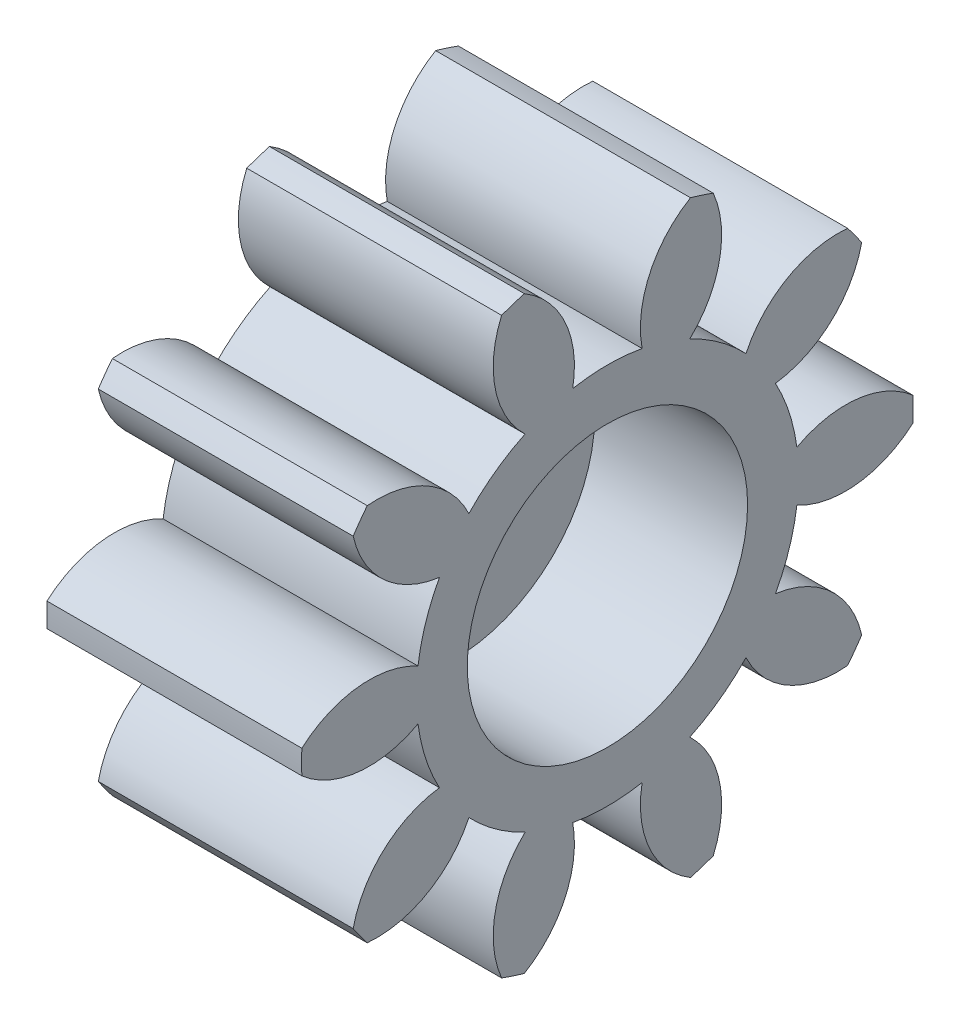
SolidWorks part; units mm, degrees
ref_plane "Plane1" through (0, 0, 0) normal (0, 0, 1) x (1, 0, 0)
ref_plane "Plane2" through (0, 0, 0) normal (0, 1, 0) x (1, 0, 0)
ref_plane "Plane3" through (0, 0, 0) normal (1, 0, 0) x (0, 0, -1)
sketch "HoldingSke" plane through (0, 0, 0) normal (0, 1, 0) x (1, 0, 0)
  line L0 (0, 0) -> (0.9848, -0.1736)
  line L1 (-15, 0) -> (100, 0) construction
  line L2 (0, 0) -> (-2.1039, 2.3779)
  line L3 (0, 0) -> (-11.863, 4.5341)
  line L4 (0, 0) -> (8.5048, 1.4996)
  line L5 (0, 0) -> (-46.8476, -17.4728)
  line L6 (0, 0) -> (-4.1448, -2.7965)
  line L7 (-2.1039, 2.3779) -> (8.6586, 51.2059)
  line L8 (-76.2, 54.61) -> (-75.7, 54.61)
  line L9 (-67.7845, 28.3722) -> (-49.3413, 33.142)
  line L10 (-76.2, 71.12) -> (104.1128, 71.12)
  line L11 (0, 0) -> (-5, 0)
  line L12 (-76.2, 101.6) -> (-76.162, 101.6)
  line L13 (24.9733, 27.94) -> (52.9518, 28.4284)
  line L14 (24.9733, 27.94) -> (24.9743, 27.94)
  line L15 (24.9733, 27.94) -> (100.4006, 29.5858)
  line L16 (-63.627, -1) -> (-12.827, -1)
  circle A0 centre (0, 0) radius 1.5
  circle A1 centre (0, 0) radius 3.749
  circle A2 centre (0, 0) radius 37.5
  circle A3 centre (0, 0) radius 1.5
  dimension "MHD" = 7.498
  dimension "Hub_dia" = 75
  dimension "Bore" = 3
  dimension "MBD" = 3
  dimension "Num_teeth" = 10
  dimension "Pitch" = 1
  dimension "Overall_len" = 50
  dimension "Show_teeth" = 10
  dimension "Thickness" = 5
  dimension "OAL" = 50.0001
  dimension "T_dim" = 0.5
  dimension "Ap" = 14.5
  dimension "H" = 19.05
  dimension "Pitch_radius" = 180.3128
  dimension "Width" = 5
  dimension "Backlash" = 0.038
  dimension "Addendum_fac" = 1
  dimension "Dedendum_fac" = 1.25
  dimension "Clearance_fac" = 0.25
  dimension "Dedendum_add" = 0.001
  dimension "Module" = 1
sketch "BasProSke" plane through (0, 0, 0) normal (0, 1, 0) x (1, 0, 0)
  line L0 (-10, 0) -> (60, 0) construction
  line L1 (0, 0) -> (0, 6)
  line L2 (0, 0) -> (5, 0)
  line L3 (5, 0) -> (5, 6)
  line L4 (5, 6) -> (0, 6)
  dimension "Thickness" = 5
  dimension "Diameter" = 12
revolve "Base-Revolve" add sketch "BasProSke" angle 360 about L0
sketch "TooCutSke" plane through (0, 0, 0) normal (1, 0, 0) x (0, 0, -1)
  line L1 (0, 0) -> (0, 107) construction
  line L2 (0, 0) -> (-0.8485, 4.9275) construction
  line L3 (0, 0) -> (-3.0584, 9.4126) construction
  line L4 (-0.8485, 4.9275) -> (-1.5292, 4.7063) construction
  arc A0 (0.6809, 3.6866) -> (-0.6809, 3.6866) centre (0, 0) ccw
  arc A1 (1.66, 5.7922) -> (-1.66, 5.7922) centre (0, 0) ccw
  circle A2 centre (0, 0) radius 5 construction
  circle A3 centre (0, 0) radius 4.8407 construction
  arc A4 (-0.6809, 3.6866) -> (-1.66, 5.7922) centre (-2.6471, 4.0528) ccw
  arc A5 (1.66, 5.7922) -> (0.6809, 3.6866) centre (2.6471, 4.0528) ccw
  dimension "Root_dia" = 7.498
  dimension "Overcut_dia" = 12.0508
  dimension "Pitch_dia" = 10
  dimension "Base_dia" = 9.6815
  dimension "Flank_rad" = 2
  dimension "Half_ang" = 18
  dimension "Half_CT" = 0.7157
extrude "ToothCut" cut sketch "TooCutSke" along normal through all
fillet "Breaks" [suppressed] radius 0.02
fillet "RootFillets" [suppressed] radius 0.251
pattern_circular "TeethCuts" count 10 every 36 about axis through (-10, 0, 0) along (1, 0, 0) of "ToothCut", "RootFillets", "Breaks"
sketch "HubNeaOneSke" plane through (0, 0, 0) normal (-1, 0, 0) x (0, 0, 1)
  circle A0 centre (0, 0) radius 3.749
  dimension "Diameter" = 7.498
extrude "HubNearOne" [suppressed] add sketch "HubNeaOneSke" along normal blind 45.0001
sketch "HubNeaBotSke" plane through (0, 0, 0) normal (-1, 0, 0) x (0, 0, 1)
  circle A0 centre (0, 0) radius 3.749
  dimension "Diameter" = 7.498
extrude "HubNearBoth" [suppressed] add sketch "HubNeaBotSke" along normal blind 22.5
ref_plane "FarPln" through (5, 0, 0) normal (1, 0, 0) x (0, 0, -1)
sketch "HubFarSke" plane through (5, 0, 0) normal (1, 0, 0) x (0, 0, -1)
  circle A0 centre (0, 0) radius 3.749
  dimension "Diameter" = 7.498
extrude "HubFar" [suppressed] add sketch "HubFarSke" along normal blind 22.5
sketch "BorSke" plane through (0, 0, 0) normal (1, 0, 0) x (0, 0, -1)
  circle A0 centre (0, 0) radius 1.5
  dimension "Diameter" = 3
extrude "Bore" cut sketch "BorSke" along normal mid plane 100.0001
sketch "KeySke" plane through (0, 0, 0) normal (1, 0, 0) x (0, 0, -1)
  line L0 (-0.6, 0) -> (-0.6, 2)
  line L1 (-0.6, 2) -> (0.6, 2)
  line L2 (0.6, 2) -> (0.6, 0)
  line L3 (0, 0) -> (0, 34) construction
  line L4 (-0.6, 0) -> (0.6, 0)
  dimension "Offset" = 2
  dimension "Width" = 1.2
extrude "Keyway" [suppressed] cut sketch "KeySke" along normal mid plane 100.0001
pattern_circular "Keyway2" [suppressed] count 2 every 90 about axis through (-10, 0, 0) along (1, 0, 0)
sketch "Esquisse1" plane through (5, 0, 0) normal (1, 0, 0) x (0, 0, -1)
  circle A0 centre (0, 0) radius 2.75
  dimension "D1" = 5.5
extrude "Enlèv. mat.-Extru.1" cut sketch "Esquisse1" against normal blind 3
equation "' \"Module@HoldingSke\" = 6.35"
equation "' \"Num_teeth@HoldingSke\" = 12"
equation "' \"Ap@HoldingSke\" =  20"
equation "' \"Ap@HoldingSke\" = 20"
equation "' \"Width@HoldingSke\" = 0.5 * 25.4"
equation "' \"Hub_dia@HoldingSke\"= 1 * 25.4"
equation "' \"Hub_dia@HoldingSke\" = 1 * 25.4"
equation "' \"Overall_len@HoldingSke\" = 1.0 * 25.4"
equation "' \"Bore@HoldingSke\" = 0.75 * 25.4"
equation "' \"T_dim@HoldingSke\" = 0.1 * 25.4"
equation "' \"Width@KeySke\" = 0.25 * 25.4"
equation "' \"Show_teeth@HoldingSke\" = 13"
equation "' \"Backlash@HoldingSke\" = 0.009 * 25.4"
equation "' \"Addendum_fac@HoldingSke\" = 1.0"
equation "' \"Dedendum_fac@HoldingSke\" = 1.25"
equation "' \"Dedendum_add@HoldingSke\" = 0.00005 * 25.4"
equation "' \"Clearance_fac@HoldingSke\" = 0.25"
equation "\"Pitch@HoldingSke\" = 1 / \"Module@HoldingSke\""
equation "\"Overcut_dia@TooCutSke\" = (\"Num_teeth@HoldingSke\" + 2 * \"Addendum_fac@HoldingSke\") / \"Pitch@HoldingSke\" + 0.002 * 25.4"
equation "\"Pitch_dia@TooCutSke\" = \"Num_teeth@HoldingSke\" / \"Pitch@HoldingSke\""
equation "\"Base_dia@TooCutSke\" = \"Num_teeth@HoldingSke\" / \"Pitch@HoldingSke\" * cos((\"Ap@HoldingSke\"  * 3.14159265 / 180))"
equation "\"Root_dia@TooCutSke\" = (\"Num_teeth@HoldingSke\" + 2) / \"Pitch@HoldingSke\" - 2 * (\"Addendum_fac@HoldingSke\" + \"Dedendum_fac@HoldingSke\") / \"Pitch@HoldingSke\" - \"Dedendum_add@HoldingSke\" * 2"
equation "\"Half_ang@TooCutSke\" = 180 / \"Num_teeth@HoldingSke\""
equation "\"Half_CT@TooCutSke\" = \"Num_teeth@HoldingSke\" / \"Pitch@HoldingSke\" * sin((3.14159265 / 2 / \"Num_teeth@HoldingSke\")) / 2 - 7 * \"Backlash@HoldingSke\" / 4"
equation "\"Flank_rad@TooCutSke\" = \"Num_teeth@HoldingSke\" / \"Pitch@HoldingSke\" / 5"
equation "\"Radius@RootFillets\" = \"Clearance_fac@HoldingSke\" / \"Pitch@HoldingSke\" + \"Dedendum_add@HoldingSke\""
equation "\"Break_rad@Breaks\" = 0.02 / \"Pitch@HoldingSke\""
equation "\"Thickness@HoldingSke\" = \"Width@HoldingSke\""
equation "\"OAL@HoldingSke\" = \"Thickness@HoldingSke\""
equation "\"MHD@HoldingSke\" = (\"Num_teeth@HoldingSke\" + 2) / \"Pitch@HoldingSke\" - 2 * (\"Addendum_fac@HoldingSke\" + \"Dedendum_fac@HoldingSke\")  / \"Pitch@HoldingSke\" - \"Dedendum_add@HoldingSke\" * 2"
equation "\"MBD@HoldingSke\" = (\"Num_teeth@HoldingSke\" + 2) / \"Pitch@HoldingSke\" - 2 * (\"Addendum_fac@HoldingSke\" + \"Dedendum_fac@HoldingSke\")  / \"Pitch@HoldingSke\" - \"Dedendum_add@HoldingSke\" * 2 - 0.002 * 25.4"
equation "\"MHD@HoldingSke\" = ((sgn( \"MHD@HoldingSke\" - \"Hub_dia@HoldingSke\" )-1)*( \"MHD@HoldingSke\" - \"Hub_dia@HoldingSke\" ))/-2+ \"Hub_dia@HoldingSke\""
equation "\"MBD@HoldingSke\" = ((sgn( \"MBD@HoldingSke\" - \"Bore@HoldingSke\" )-1)*( \"MBD@HoldingSke\" - \"Bore@HoldingSke\" ))/-2+ \"Bore@HoldingSke\""
equation "\"OAL@HoldingSke\" = ((sgn( \"OAL@HoldingSke\" - \"Overall_len@HoldingSke\" )+1)*( \"OAL@HoldingSke\" - \"Overall_len@HoldingSke\" ))/2 + \"Overall_len@HoldingSke\" + 0.000002 * 25.4"
equation "\"Num_teeth@TeethCuts\" = int( \"Show_teeth@HoldingSke\" ) + 1"
equation "\"Num_teeth@TeethCuts\" = ((sgn( \"Num_teeth@TeethCuts\" - \"Num_teeth@HoldingSke\" )-1)*( \"Num_teeth@TeethCuts\" - \"Num_teeth@HoldingSke\" ))/-2+ \"Num_teeth@HoldingSke\""
equation "\"Num_teeth@TeethCuts\" = ((sgn( \"Num_teeth@TeethCuts\" - 2.0)+1)*( \"Num_teeth@TeethCuts\" - 2.0))/2 +2.0"
equation "\"Angle@TeethCuts\" = 360.0 / \"Num_teeth@HoldingSke\""
equation "\"Diameter@BasProSke\" = (\"Num_teeth@HoldingSke\" + 2 * \"Addendum_fac@HoldingSke\") / \"Pitch@HoldingSke\""
equation "\"Thickness@BasProSke\"  = \"Thickness@HoldingSke\""
equation "' \"Fillet_rad@BasProSke\" =  \"Thickness@HoldingSke\" * 0.05"
equation "' \"Fillet_rad@BasProSke\" = \"Thickness@HoldingSke\" * 0.05"
equation "\"MHD@HoldingSke\" = ((sgn( \"MHD@HoldingSke\" - \"Root_dia@TooCutSke\" )-1)*( \"MHD@HoldingSke\" - \"Root_dia@TooCutSke\" ))/-2+ \"Root_dia@TooCutSke\""
equation "\"Diameter@HubNeaOneSke\" = \"MHD@HoldingSke\""
equation "\"Length@HubNearOne\" = \"OAL@HoldingSke\" - \"Thickness@BasProSke\""
equation "\"Diameter@HubNeaBotSke\" = \"MHD@HoldingSke\""
equation "\"Length@HubNearBoth\" = ( \"OAL@HoldingSke\" - \"Thickness@BasProSke\" ) / 2.0"
equation "\"Thickness@FarPln\" = \"Thickness@BasProSke\""
equation "\"Diameter@HubFarSke\" = \"MHD@HoldingSke\""
equation "\"Length@HubFar\" = ( \"OAL@HoldingSke\" - \"Thickness@BasProSke\" ) / 2.0"
equation "\"Diameter@BorSke\" = \"MBD@HoldingSke\""
equation "\"D1@Bore\" = \"OAL@HoldingSke\" * 2.0"
equation "\"D1@Keyway\" = \"OAL@HoldingSke\" * 2.0"
equation "\"Offset@KeySke\" = \"T_dim@HoldingSke\" + \"MBD@HoldingSke\" / 2.0"
